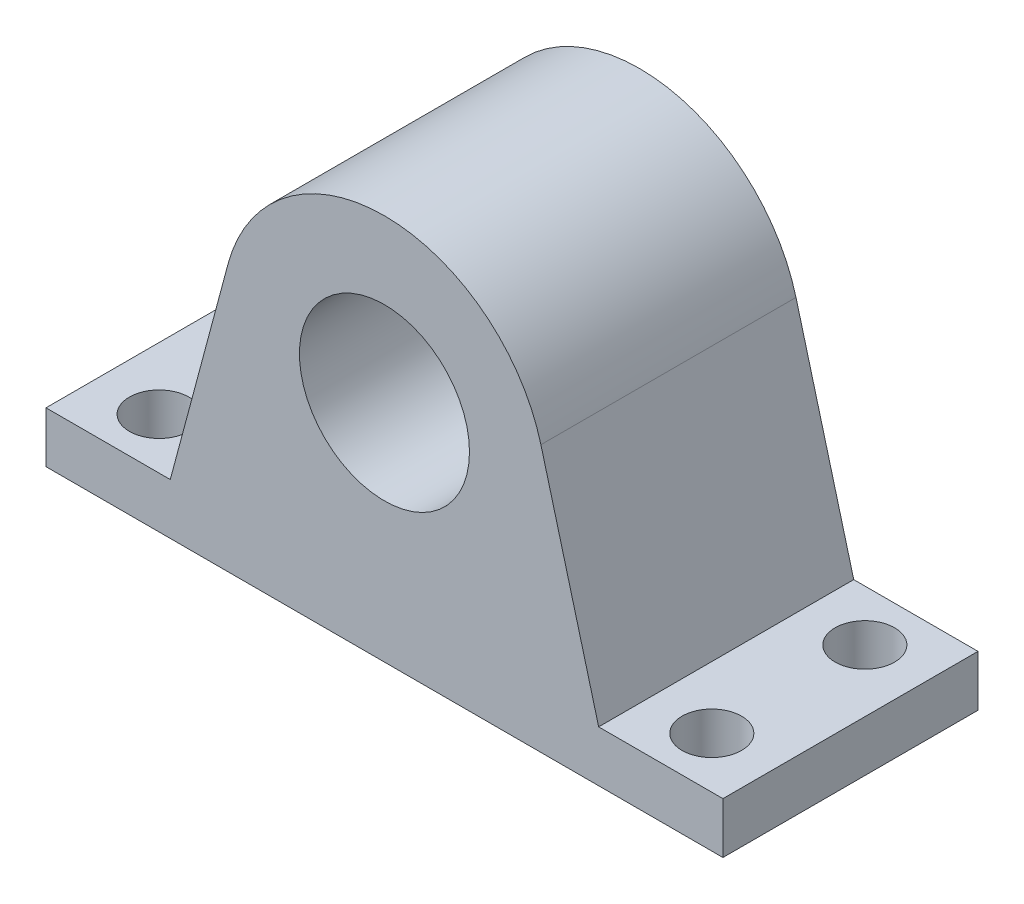
SolidWorks part; units mm, degrees
ref_plane "Front Plane" through (0, 0, 0) normal (0, 0, 1) x (1, 0, 0)
ref_plane "Top Plane" through (0, 0, 0) normal (0, 1, 0) x (1, 0, 0)
ref_plane "Right Plane" through (0, 0, 0) normal (1, 0, 0) x (0, 0, -1)
sketch "Sketch1" plane through (0, 0, 0) normal (0, 0, 1) x (1, 0, 0)
  line L0 (0, 0) -> (-39.8075, 0)
  line L3 (0, 0) -> (0, 26.416) construction
  line L5 (0, 0) -> (39.8075, 0)
  line L12 (-25.1925, 6) -> (-18.4009, 31.3465)
  line L13 (18.4009, 31.3465) -> (25.1925, 6)
  line L15 (-25.1925, 6) -> (-39.8075, 6)
  line L16 (-39.8075, 6) -> (-39.8075, 0)
  line L17 (25.1925, 6) -> (39.8075, 6)
  line L18 (39.8075, 6) -> (39.8075, 0)
  arc A0 (18.4009, 31.3465) -> (-18.4009, 31.3465) centre (0, 26.416) ccw
  circle A2 centre (0, 26.416) radius 26.416 construction
  point P1 (32.5, 6)
  point P11 (-32.5, 6)
  dimension "D1" = 38.1
  dimension "D5" = 52.832
  dimension "D2" = 6
  dimension "D3" = 105
  dimension "D4" = 65
extrude "Boss-Extrude1" add sketch "Sketch1" along normal blind 30 contours A0 L12 L15 L16 L0 L5 L18 L17 L13
hole_wizard "Ø20.0mm Dowel Hole1" positions "3DSketch1" profile "Sketch3" hole size "Ø20.0" standard "ANSI Metric"
sketch3d "3DSketch1"
  line L0 (0, 26.416, 30) -> (0, 26.416, 0) construction
  point P0 (0, 26.416, 30)
sketch "Sketch3" plane through (0, 26.416, 30) normal (1, 0, 0) x (0, -1, 0)
  line L0 (0, 0) -> (0, 80.0877)
  line L1 (0, 80.0877) -> (10, 74.0791)
  line L2 (10, 74.0791) -> (10, 0)
  line L5 (10, 0) -> (0, 0)
  line L10 (0, 80.0877) -> (-10, 74.0791) construction
  line L11 (0, -6.35) -> (0, 107.95) construction
  dimension "Hole Dia." = 20
  dimension "Hole Depth" = 74.0791
  dimension "Drill Angle" = 118
sketch "Sketch4" plane through (0, 6, 0) normal (0, 1, 0) x (1, 0, 0)
  line L0 (-32.5, -6) -> (-32.5, -24) construction
  line L1 (-25.1925, 0) -> (-39.8075, 0) construction
  line L2 (-25.1925, 0) -> (-39.8075, 0) construction
  line L3 (-39.8075, -30) -> (-39.8075, 0) construction
  line L4 (-39.8075, -30) -> (-39.8075, 0) construction
  line L5 (-39.8075, -15) -> (-32.5, -15) construction
  point P0 (-32.5, -6)
  point P1 (-32.5, -24)
  dimension "D1" = 18
hole_wizard "M8x1.0 Tapped Hole1" positions "3DSketch2" profile "Sketch6" tap size "M8x1.0" standard "ANSI Metric"
sketch3d "3DSketch2"
  point P0 (-32.5, 6, 6)
  point P3 (-32.5, 6, 24)
sketch "Sketch6" plane through (-32.5, 6, 6) normal (1, 0, 0) x (0, 0, 1)
  line L0 (0, 0) -> (0, 21.103)
  line L1 (0, 21.103) -> (3.5, 19)
  line L2 (3.5, 19) -> (3.5, 0)
  line L5 (3.5, 0) -> (0, 0)
  line L10 (0, 21.103) -> (-3.5, 19) construction
  line L11 (0, -6.35) -> (0, 107.95) construction
  dimension "Tap Drill Dia." = 7
  dimension "Tap Drill Depth" = 19
  dimension "Drill Angle" = 118
cosmetic thread "Hole Thread1" parameters "D1"=16, "D2"=8
cosmetic thread "Hole Thread2" parameters "D1"=16, "D2"=8
mirror "Mirror1" about plane through (0, 0, 0) normal (1, 0, 0) of "M8x1.0 Tapped Hole1"
cosmetic thread "Hole Thread3" parameters "D1"=16, "D2"=8
cosmetic thread "Hole Thread4" parameters "D1"=16, "D2"=8
